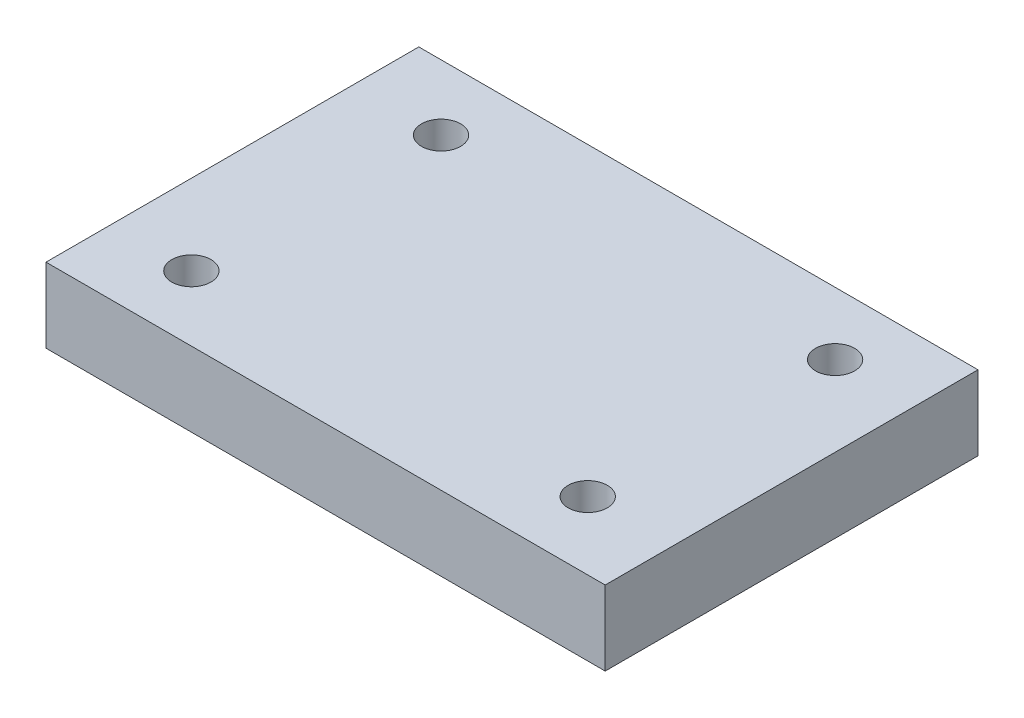
SolidWorks part; units mm, degrees
ref_plane "Front Plane" through (0, 0, 0) normal (0, 0, 1) x (1, 0, 0)
ref_plane "Top Plane" through (0, 0, 0) normal (0, 1, 0) x (1, 0, 0)
ref_plane "Right Plane" through (0, 0, 0) normal (1, 0, 0) x (0, 0, -1)
sketch "Sketch1" plane through (0, 0, 0) normal (0, 1, 0) x (1, 0, 0)
  line L1 (0, 0) -> (30, 0)
  line L2 (0, 0) -> (0, 20)
  line L3 (0, 20) -> (30, 20)
  line L4 (30, 0) -> (30, 20)
  dimension "D1" = 30
  dimension "D2" = 20
extrude "Boss-Extrude1" add sketch "Sketch1" along normal blind 4
sketch "Sketch2" plane through (0, 4, 0) normal (0, 1, 0) x (1, 0, 0)
  line L0 (30, 20) -> (0, 20) construction
  circle A0 centre (4.6937, 16.5) radius 1.05
  circle A1 centre (25.6937, 16.6392) radius 1.05
  circle A2 centre (4.3025, 3.4966) radius 1.05
  circle A3 centre (25.4232, 3.6392) radius 1.05
  point P12 (0, 14.6682)
  point P13 (0, 15.1242)
  dimension "D2" = 2.1
  dimension "D1" = 21
  dimension "D3" = 13.0034
  dimension "D4" = 13
  dimension "D5" = 3.5
extrude "Cut-Extrude2" cut sketch "Sketch2" against normal blind 10 contours A2 | A0 | A3 | A1
